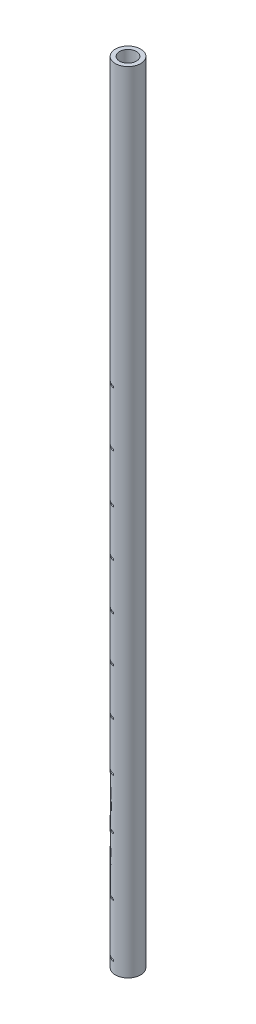
SolidWorks part; units mm, degrees
material "PPE"
ref_plane "Спереди" through (0, 0, 0) normal (0, 0, 1) x (1, 0, 0)
ref_plane "Сверху" through (0, 0, 0) normal (0, 1, 0) x (1, 0, 0)
ref_plane "Справа" through (0, 0, 0) normal (1, 0, 0) x (0, 0, -1)
sketch "Эскиз1" plane through (0, 0, 0) normal (0, 1, 0) x (1, 0, 0)
  circle A0 centre (0, 0) radius 12
  circle A1 centre (0, 0) radius 8
  dimension "D1" = 24
  dimension "D2" = 16
extrude "Бобышка-Вытянуть1" add sketch "Эскиз1" along normal blind 750
sketch "Эскиз2" plane through (0, 0, 0) normal (0, 0, 1) x (1, 0, 0)
  line L0 (-12, 750) -> (-12, 0) construction
  line L1 (-12, 10) -> (-2, 10)
  line L2 (-12, 10) -> (-12, 11.5)
  line L3 (-12, 11.5) -> (-2, 11.5)
  line L4 (-2, 10) -> (-2, 11.5)
  line L5 (-12, 0) -> (12, 0) construction
  line L6 (0, 0) -> (50000, 0) construction
  line L7 (-12, 60) -> (-2, 60)
  line L8 (-12, 60) -> (-12, 61.5)
  line L9 (-12, 61.5) -> (-2, 61.5)
  line L10 (-2, 60) -> (-2, 61.5)
  line L11 (-12, 115) -> (-2, 115)
  line L12 (-12, 115) -> (-12, 116.5)
  line L13 (-12, 116.5) -> (-2, 116.5)
  line L14 (-2, 115) -> (-2, 116.5)
  line L15 (-12, 163) -> (-2, 163)
  line L16 (-12, 163) -> (-12, 164.5)
  line L17 (-12, 164.5) -> (-2, 164.5)
  line L18 (-2, 163) -> (-2, 164.5)
  line L19 (-12, 209) -> (-2, 209)
  line L20 (-12, 209) -> (-12, 210.5)
  line L21 (-12, 210.5) -> (-2, 210.5)
  line L22 (-2, 209) -> (-2, 210.5)
  line L23 (-12, 253) -> (-2, 253)
  line L24 (-12, 253) -> (-12, 254.5)
  line L25 (-12, 254.5) -> (-2, 254.5)
  line L26 (-2, 253) -> (-2, 254.5)
  line L27 (-12, 296) -> (-2, 296)
  line L28 (-12, 296) -> (-12, 297.5)
  line L29 (-12, 297.5) -> (-2, 297.5)
  line L30 (-2, 296) -> (-2, 297.5)
  line L31 (-12, 340) -> (-2, 340)
  line L32 (-12, 340) -> (-12, 341.5)
  line L33 (-12, 341.5) -> (-2, 341.5)
  line L34 (-2, 340) -> (-2, 341.5)
  line L35 (-12, 384) -> (-2, 384)
  line L36 (-12, 384) -> (-12, 385.5)
  line L37 (-12, 385.5) -> (-2, 385.5)
  line L38 (-2, 384) -> (-2, 385.5)
  line L39 (-12, 430) -> (-2, 430)
  line L40 (-12, 430) -> (-12, 431.5)
  line L41 (-12, 431.5) -> (-2, 431.5)
  line L42 (-2, 430) -> (-2, 431.5)
  line L43 (-12, 482) -> (-2, 482)
  line L44 (-12, 482) -> (-12, 483.5)
  line L45 (-12, 483.5) -> (-2, 483.5)
  line L46 (-2, 482) -> (-2, 483.5)
  dimension "D1" = 1.5
  dimension "D2" = 10
  dimension "D3" = 10
  dimension "D4" = 60
  dimension "D5" = 115
  dimension "D6" = 163
  dimension "D7" = 209
  dimension "D8" = 253
  dimension "D9" = 296
  dimension "D10" = 340
  dimension "D11" = 384
  dimension "D12" = 430
  dimension "D13" = 482
extrude "Вырез-Вытянуть1" cut sketch "Эскиз2" against normal mid plane 40
sketch "Эскиз3" plane through (-2, 0, 0) normal (-1, 0, 0) x (0, 0, 1)
  line L0 (11.8322, 10.75) -> (-11.8322, 10.75) construction
  line L1 (11.8322, 11.5) -> (11.8322, 10) construction
  line L2 (-11.8322, 10) -> (-11.8322, 11.5) construction
  line L3 (11.8322, 60.75) -> (-11.8322, 60.75) construction
  line L4 (11.8322, 115.75) -> (-11.8322, 115.75) construction
  line L5 (11.8322, 163.75) -> (-11.8322, 163.75) construction
  line L6 (11.8322, 209.75) -> (-11.8322, 209.75) construction
  line L7 (11.8322, 253.75) -> (-11.8322, 253.75) construction
  line L8 (11.8322, 296.75) -> (-11.8322, 296.75) construction
  line L9 (11.8322, 340.75) -> (-11.8322, 340.75) construction
  line L10 (11.8322, 384.75) -> (-11.8322, 384.75) construction
  line L11 (11.8322, 430.75) -> (-11.8322, 430.75) construction
  line L12 (11.8322, 482.75) -> (-11.8322, 482.75) construction
  circle A0 centre (0, 10.75) radius 2
  circle A1 centre (0, 60.75) radius 2
  circle A2 centre (0, 115.75) radius 2
  circle A3 centre (0, 163.75) radius 2
  circle A4 centre (0, 209.75) radius 2
  circle A5 centre (0, 253.75) radius 2
  circle A6 centre (0, 296.75) radius 2
  circle A7 centre (0, 340.75) radius 2
  circle A8 centre (0, 384.75) radius 2
  circle A9 centre (0, 430.75) radius 2
  circle A10 centre (0, 482.75) radius 2
  dimension "D1" = 4
extrude "Вырез-Вытянуть2" cut sketch "Эскиз3" along normal blind 40
